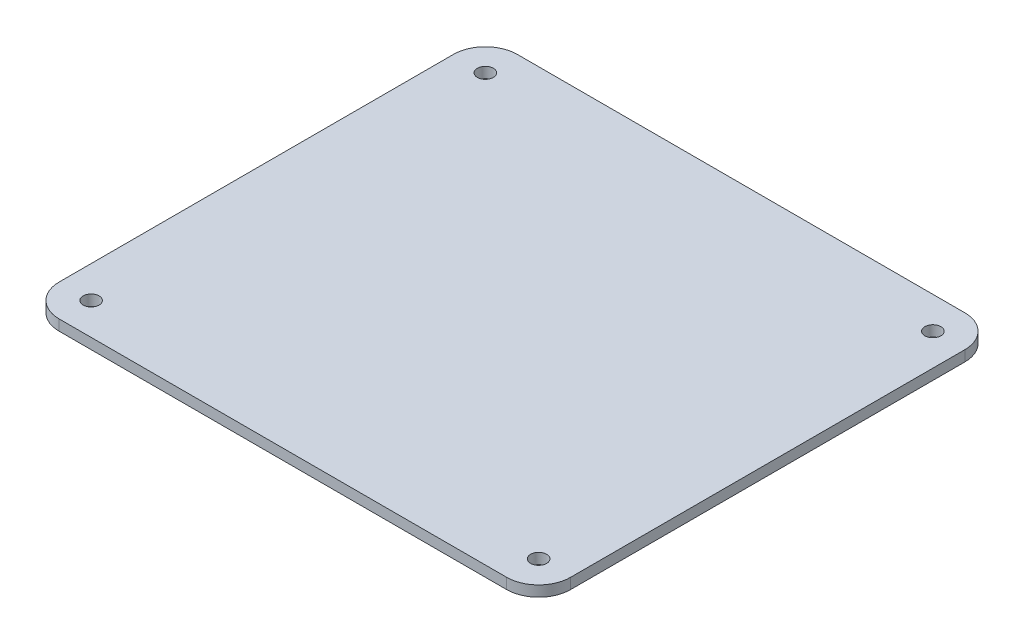
SolidWorks part; units mm, degrees
ref_plane "Front Plane" through (0, 0, 0) normal (0, 0, 1) x (1, 0, 0)
ref_plane "Top Plane" through (0, 0, 0) normal (0, 1, 0) x (1, 0, 0)
ref_plane "Right Plane" through (0, 0, 0) normal (1, 0, 0) x (0, 0, -1)
sketch "Sketch1" plane through (0, 0, 0) normal (0, 1, 0) x (1, 0, 0)
  line L5 (-42, -43) -> (42, -43)
  line L6 (-48, -37) -> (-48, 37)
  line L7 (-42, 43) -> (42, 43)
  line L8 (48, -37) -> (48, 37)
  line L9 (-48, -43) -> (48, 43) construction
  line L10 (-48, 43) -> (48, -43) construction
  arc A4 (-42, -43) -> (-48, -37) centre (-42, -37) cw
  arc A5 (42, -43) -> (48, -37) centre (42, -37) ccw
  arc A6 (42, 43) -> (48, 37) centre (42, 37) cw
  arc A7 (-48, 37) -> (-42, 43) centre (-42, 37) cw
  circle A8 centre (-42, 37) radius 1.5
  circle A9 centre (42, 37) radius 1.5
  circle A10 centre (42, -37) radius 1.5
  circle A11 centre (-42, -37) radius 1.5
  point P12 (0, 0)
  dimension "D3" = 3
  dimension "D6" = 6
  dimension "D1" = 3
  dimension "D2" = 3
  dimension "D7" = 3
  dimension "D4" = 96
  dimension "D5" = 86
extrude "Boss-Extrude1" add sketch "Sketch1" along normal blind 2
